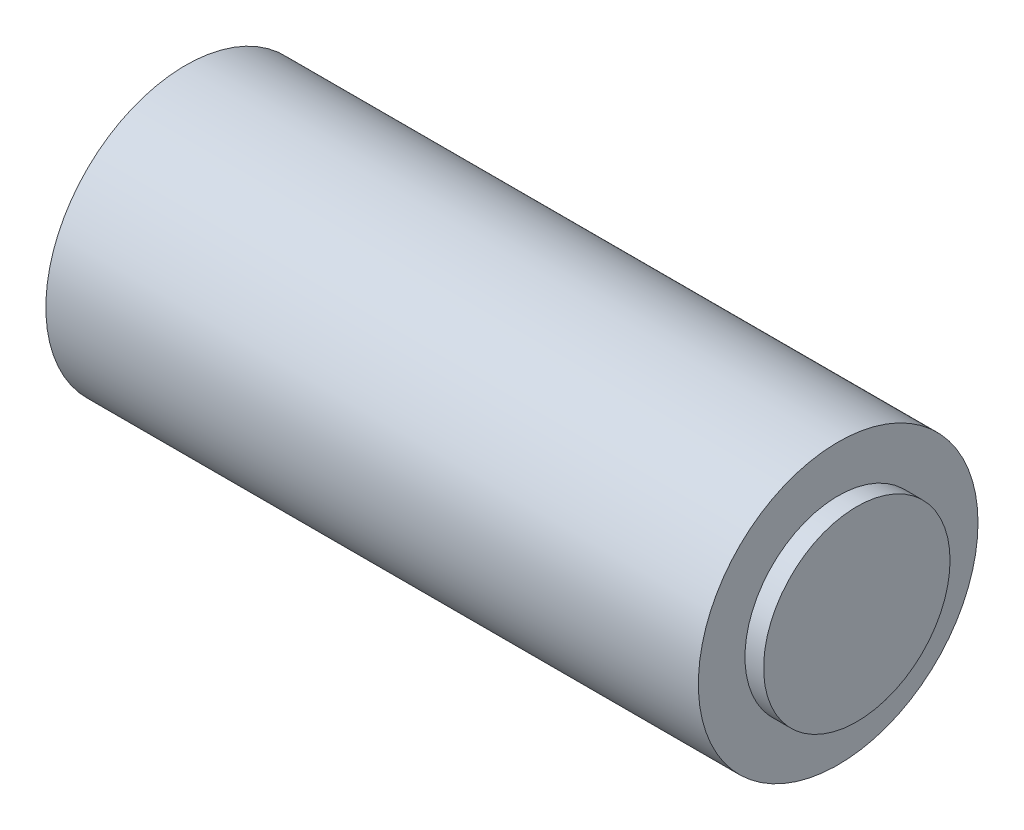
SolidWorks part; units mm, degrees
material "Beryllium Copper, UNS C17000"
ref_plane "Front Plane" through (0, 0, 0) normal (0, 0, 1) x (1, 0, 0)
ref_plane "Top Plane" through (0, 0, 0) normal (0, 1, 0) x (1, 0, 0)
ref_plane "Right Plane" through (0, 0, 0) normal (1, 0, 0) x (0, 0, -1)
sketch "Sketch1" plane through (0, 0, 0) normal (0, 1, 0) x (1, 0, 0)
  line L0 (0, 0) -> (0, -5)
  line L1 (0, -5) -> (-1, -5)
  line L2 (-1, -5) -> (-1, -7.5)
  line L3 (-1, -7.5) -> (34, -7.5)
  line L4 (34, -7.5) -> (34, -5)
  line L5 (34, -5) -> (35, -5)
  line L6 (35, -5) -> (35, 0)
  line L7 (35, 0) -> (0, 0) construction
  line L8 (0, 0) -> (35, 0)
  dimension "D1" = 35
  dimension "D2" = 7.5
  dimension "D3" = 1
  dimension "D4" = 2.5
  dimension "D5" = 2.5
  dimension "D6" = 1
  dimension "D7" = 7.5
revolve "Revolve1" add sketch "Sketch1" angle 360 about L7
